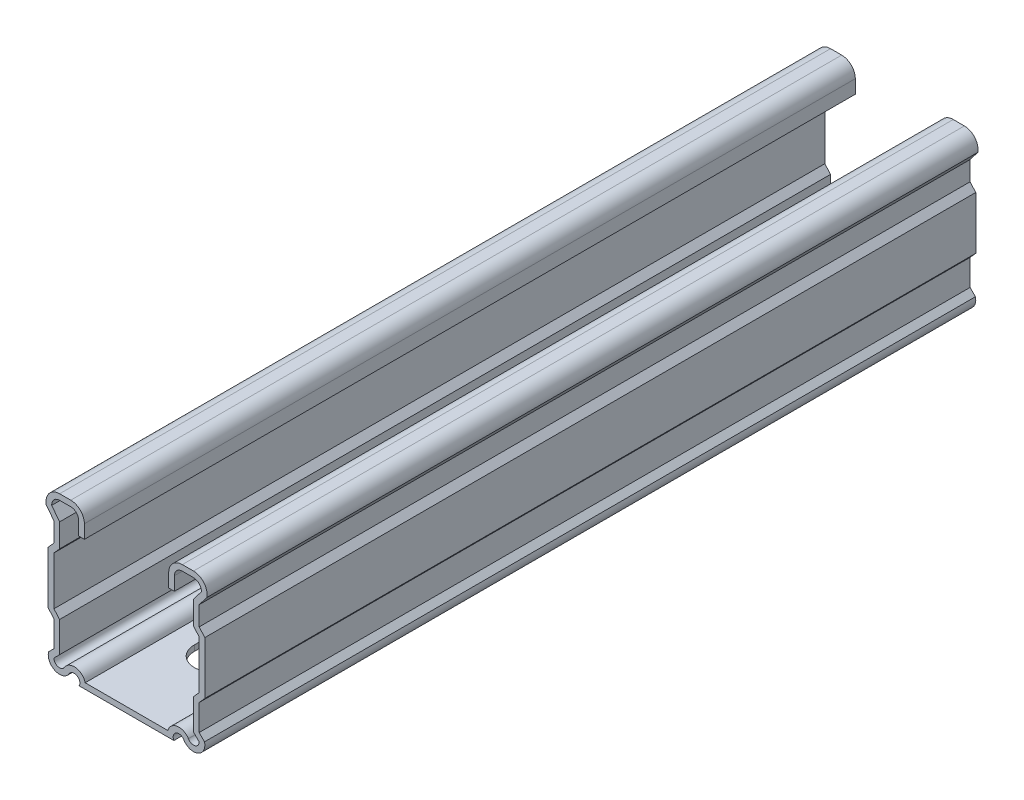
SolidWorks part; units mm, degrees
ref_plane "Plane1" through (0, 0, 0) normal (0, 0, 1) x (1, 0, 0)
ref_plane "Plane2" through (0, 0, 0) normal (0, 1, 0) x (1, 0, 0)
ref_plane "Plane3" through (0, 0, 0) normal (1, 0, 0) x (0, 0, -1)
sketch "Sketch1" plane through (0, 0, 0) normal (0, 0, 1) x (1, 0, 0)
  line L0 (17.6403, 16.3393) -> (19.7299, 19.0635)
  line L1 (17.6403, -13.9795) -> (19.1389, -15.4781)
  line L2 (-17.6403, -13.9795) -> (-19.1389, -15.4781)
  line L4 (-17.6403, -13.9795) -> (-17.6403, -5.9368)
  line L5 (17.6403, 21.2598) -> (14.7033, 21.2598)
  line L6 (12.6111, 19.1676) -> (12.6111, 15.6147)
  line L7 (-17.6403, -5.9368) -> (-19.1389, -4.2539)
  line L8 (-12.6111, 19.1676) -> (-12.6111, 15.6147)
  line L9 (0, 10.16) -> (0, -7.62) construction
  line L10 (-19.1389, -4.2539) -> (-19.1389, 8.4957)
  line L11 (-17.6403, 10.1786) -> (-19.1389, 8.4957)
  line L12 (-17.6403, 10.1786) -> (-17.6403, 16.3393)
  line L13 (-17.6403, 16.3393) -> (-19.7299, 19.0635)
  line L14 (-17.6403, 21.2598) -> (-14.7033, 21.2598)
  line L16 (17.6403, -13.9795) -> (17.6403, -5.9368)
  line L17 (17.6403, 10.1786) -> (17.6403, 16.3393)
  line L18 (-11.1125, 19.1676) -> (-11.1125, 15.6147)
  line L19 (-17.6403, 22.7584) -> (-14.7033, 22.7584)
  line L20 (-19.1389, 15.8307) -> (-21.1624, 18.4689)
  line L21 (-19.1389, 10.7491) -> (-19.1389, 15.8307)
  line L22 (-19.1389, 10.7491) -> (-20.6375, 9.0662)
  line L23 (-20.6375, -4.8244) -> (-20.6375, 9.0662)
  line L24 (-19.1389, -6.5073) -> (-20.6375, -4.8244)
  line L25 (19.1389, -4.2539) -> (19.1389, 8.4957)
  line L26 (-19.1389, -13.3588) -> (-19.1389, -6.5073)
  line L27 (-19.1389, -13.3588) -> (-20.5535, -14.7733)
  line L28 (11.1125, 19.1676) -> (11.1125, 15.6147)
  line L29 (17.6403, 22.7584) -> (14.7033, 22.7584)
  line L30 (19.1389, 15.8307) -> (21.1624, 18.4689)
  line L31 (19.1389, 10.7491) -> (19.1389, 15.8307)
  line L32 (19.1389, 10.7491) -> (20.6375, 9.0662)
  line L33 (20.6375, -4.8244) -> (20.6375, 9.0662)
  line L34 (19.1389, -6.5073) -> (20.6375, -4.8244)
  line L35 (19.1389, -13.3588) -> (19.1389, -6.5073)
  line L36 (19.1389, -13.3588) -> (20.5535, -14.7733)
  line L37 (17.6403, -5.9368) -> (19.1389, -4.2539)
  line L38 (-12.4806, -18.5166) -> (12.4806, -18.5166)
  line L39 (17.6403, 10.1786) -> (19.1389, 8.4957)
  line L41 (-10.899, -17.018) -> (10.899, -17.018)
  line L42 (-12.6111, 15.6147) -> (-11.1125, 15.6147)
  line L43 (11.1125, 15.6147) -> (12.6111, 15.6147)
  arc A0 (19.1389, -15.4781) -> (16.3052, -16.1588) centre (17.6403, -15.4781) cw
  arc A1 (16.3052, -16.1588) -> (10.899, -17.018) centre (13.7938, -17.7947) ccw
  arc A2 (-16.4143, -16.3399) -> (-10.899, -17.018) centre (-13.7938, -17.7947) cw
  arc A3 (-19.1389, -15.4781) -> (-16.4143, -16.3399) centre (-17.6403, -15.4781) ccw
  arc A4 (-17.6403, 21.2598) -> (-19.7299, 19.0635) centre (-17.6403, 19.1676) ccw
  arc A5 (-12.6111, 19.1676) -> (-14.7033, 21.2598) centre (-14.7033, 19.1676) ccw
  arc A6 (17.6403, 21.2598) -> (19.7299, 19.0635) centre (17.6403, 19.1676) cw
  arc A7 (12.6111, 19.1676) -> (14.7033, 21.2598) centre (14.7033, 19.1676) cw
  arc A8 (-11.1125, 19.1676) -> (-14.7033, 22.7584) centre (-14.7033, 19.1676) ccw
  arc A9 (-17.6403, 22.7584) -> (-21.1624, 18.4689) centre (-17.6403, 19.1676) ccw
  arc A10 (-20.5535, -14.7733) -> (-15.0198, -16.9329) centre (-17.6403, -15.4781) ccw
  arc A11 (11.1125, 19.1676) -> (14.7033, 22.7584) centre (14.7033, 19.1676) cw
  arc A12 (17.6403, 22.7584) -> (21.1624, 18.4689) centre (17.6403, 19.1676) cw
  arc A13 (20.5535, -14.7733) -> (15.0198, -16.9329) centre (17.6403, -15.4781) cw
  arc A14 (15.0198, -16.9329) -> (12.4806, -18.5166) centre (13.7938, -17.7947) ccw
  arc A15 (-15.0198, -16.9329) -> (-12.4806, -18.5166) centre (-13.7938, -17.7947) cw
  dimension "D9" = 7.1437
  dimension "base" = 18.5166
  dimension "D5" = 9.525
  dimension "ToeHt" = 22.7584
  dimension "D6" = 22.225
  dimension "D8" = 15.4781
  dimension "D12" = 41.275
  dimension "D14" = 13.6922
  dimension "D15" = 13.8906
extrude "Base-Extrude" add sketch "Sketch1" along normal blind 203.2
extrude "LSlot" cut sketch "Sketch2" against normal through all
sketch "Sketch2" plane through (-0.0935, -18.5166, -16.4661) normal (0, -1, 0) x (1, 0, 0)
  line L0 (5.2528, 95.0473) -> (5.2528, 29.1661)
  line L1 (-5.0659, 29.1661) -> (-5.0659, 95.0473)
  arc A0 (-5.0659, 29.1661) -> (5.2528, 29.1661) centre (0.0935, 29.1661) ccw
  arc A1 (5.2528, 95.0473) -> (-5.0659, 95.0473) centre (0.0935, 95.0473) ccw
  dimension "D3" = 10.3187
  dimension "D1" = 12.7
  dimension "D2" = 65.8813
pattern_linear "LPattern1" count 2 spacing 101.6 along (0, 0, 1) of "LSlot"
equation "\"D1@LPattern1\" = \"D1@Base-Extrude\" / \"D3@LPattern1\""
